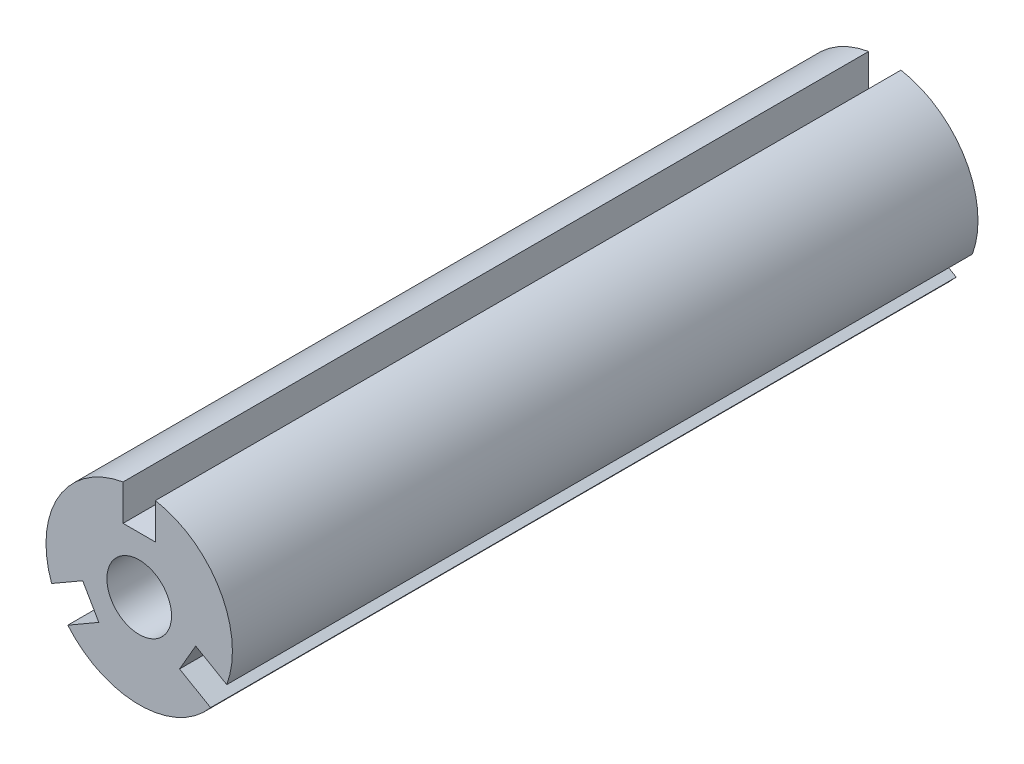
SolidWorks part; units mm, degrees
ref_plane "Piano frontale" through (0, 0, 0) normal (0, 0, 1) x (1, 0, 0)
ref_plane "Piano superiore" through (0, 0, 0) normal (0, 1, 0) x (1, 0, 0)
ref_plane "Piano destro" through (0, 0, 0) normal (1, 0, 0) x (0, 0, -1)
sketch "Schizzo1" plane through (0, 0, 0) normal (0, 0, 1) x (1, 0, 0)
  line L0 (7.0469, -2.5674) -> (4.5471, -1.1242)
  line L6 (-1.3, 7.3865) -> (-1.3, 4.5)
  line L7 (-1.3, 4.5) -> (1.3, 4.5)
  line L8 (1.3, 7.3865) -> (1.3, 4.5)
  line L9 (0, 7.5) -> (1.3, 4.5) construction
  line L10 (-1.3, 4.5) -> (0, 7.5) construction
  line L11 (4.5471, -1.1242) -> (3.2471, -3.3758)
  line L12 (5.7469, -4.8191) -> (3.2471, -3.3758)
  line L13 (-5.7469, -4.8191) -> (-3.2471, -3.3758)
  line L14 (-3.2471, -3.3758) -> (-4.5471, -1.1242)
  line L15 (-7.0469, -2.5674) -> (-4.5471, -1.1242)
  arc A0 (-5.7469, -4.8191) -> (5.7469, -4.8191) centre (0, 0) ccw
  arc A1 (7.0469, -2.5674) -> (1.3, 7.3865) centre (0, 0) ccw
  arc A2 (-1.3, 7.3865) -> (-7.0469, -2.5674) centre (0, 0) ccw
  point P3 (0, 7.5)
  point P20 (0, 0)
  dimension "D1" = 15
  dimension "D2" = 2.6
  dimension "D3" = 3
  dimension "D4" = 3
extrude "Estrusione-Estrusione1" add sketch "Schizzo1" along normal blind 60
sketch "Schizzo2" plane through (0, 0, 60) normal (0, 0, 1) x (1, 0, 0)
  circle A0 centre (0, 0) radius 2.6
  dimension "D1" = 5.2
extrude "Taglio-Estrusione1" cut sketch "Schizzo2" against normal blind 60
sketch "Schizzo3" plane through (0, 0, 0) normal (0, 1, 0) x (1, 0, 0)
  circle A0 centre (0, -30) radius 2.4
  dimension "D1" = 4.8
extrude "Taglio-Estrusione2" cut sketch "Schizzo3" against normal blind 10
